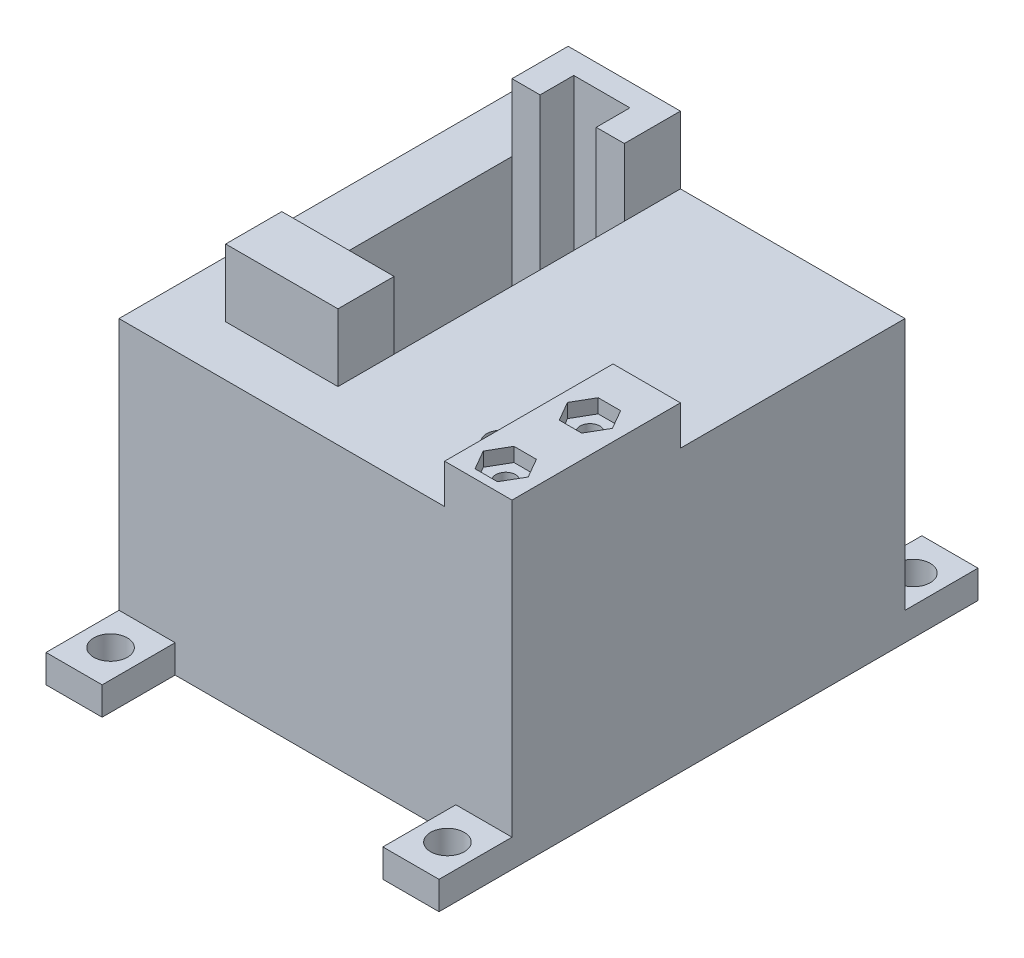
SolidWorks part; units mm, degrees
ref_plane "Front Plane" through (0, 0, 0) normal (0, 0, 1) x (1, 0, 0)
ref_plane "Top Plane" through (0, 0, 0) normal (0, 1, 0) x (1, 0, 0)
ref_plane "Right Plane" through (0, 0, 0) normal (1, 0, 0) x (0, 0, -1)
sketch "Sketch1" plane through (0, 0, 0) normal (0, 1, 0) x (1, 0, 0)
  line L1 (35, 35) -> (-35, 35)
  line L2 (35, 35) -> (35, -35)
  line L3 (35, -35) -> (-35, -35)
  line L4 (-35, 35) -> (-35, -35)
  line L5 (35, 35) -> (-35, -35) construction
  line L6 (35, -35) -> (-35, 35) construction
  point P0 (0, 0)
extrude "Boss-Extrude1" add sketch "Sketch1" along normal blind 50
sketch "Sketch2" plane through (0, 0, 0) normal (0, -1, 0) x (1, 0, 0)
  line L1 (0, 25) -> (-25, 25)
  line L2 (-25, 25) -> (-25, -25)
  line L3 (-25, -25) -> (25, -25)
  line L4 (0, 25) -> (25, 25)
  line L5 (25, 25) -> (25, -25)
extrude "Cut-Extrude1" cut sketch "Sketch2" against normal blind 40
sketch "Sketch3" plane through (0, 50, 0) normal (0, 1, 0) x (1, 0, 0)
  line L11 (-25, 25) -> (-5, 25)
  line L12 (-5, 25) -> (-5, -16)
  line L13 (-5, -16) -> (-25, -16)
  line L14 (-25, 25) -> (-25, -16)
extrude "Cut-Extrude2" cut sketch "Sketch3" against normal blind 40
sketch "Sketch4" plane through (0, 50, 0) normal (0, 1, 0) x (1, 0, 0)
  line L0 (-15, 25) -> (-15, 15)
  line L1 (-5, 25) -> (-25, 25) construction
  line L2 (-15, 15) -> (30, 15)
  line L4 (35, -35) -> (23, -35)
  line L6 (35, -35) -> (35, -5)
  line L8 (35, -5) -> (23, -5)
  line L9 (23, -35) -> (23, -5)
  line M24 (-35, -35) -> (35, -35)
  line M25 (35, -35) -> (35, 35)
extrude "Boss-Extrude2" add sketch "Sketch4" along normal blind 7 contours L9 L8 M24 M25
sketch "Sketch5" plane through (0, 57, 0) normal (0, 1, 0) x (1, 0, 0)
  line L3 (32.8817, -15) -> (30.8817, -18.4641)
  line L4 (30.8817, -18.4641) -> (26.8817, -18.4641)
  line L5 (26.8817, -18.4641) -> (24.8817, -15)
  line L6 (24.8817, -15) -> (26.8817, -11.5359)
  line L7 (26.8817, -11.5359) -> (30.8817, -11.5359)
  line L8 (30.8817, -11.5359) -> (32.8817, -15)
  line L9 (26.8817, -33.4641) -> (24.8817, -30)
  line L10 (24.8817, -30) -> (26.8817, -26.5359)
  line L11 (30.8817, -33.4641) -> (26.8817, -33.4641)
  line L12 (30.8817, -26.5359) -> (32.8817, -30)
  line L13 (32.8817, -30) -> (30.8817, -33.4641)
  line L14 (26.8817, -26.5359) -> (30.8817, -26.5359)
extrude "Cut-Extrude3" cut sketch "Sketch5" against normal blind 2.5
sketch "Sketch7" plane through (0, 50, 0) normal (0, 1, 0) x (1, 0, 0)
  line L0 (23, -35) -> (23, -20)
  line L1 (23, -35) -> (23, -5) construction
  circle A0 centre (18, -20) radius 2.5
extrude "Cut-Extrude4" cut sketch "Sketch7" against normal blind 52.5 contours A0
sketch "Sketch10" plane through (0, 0, 0) normal (0, -1, 0) x (1, 0, 0)
  line L1 (-25, -25) -> (25, -25) construction
  line L2 (-20, -25) -> (-20, -31)
  line L3 (-20, -31) -> (-10, -31)
  line L4 (-10, -31) -> (-10, -25)
  line L5 (-10, -25) -> (-20, -25)
extrude "Cut-Extrude6" cut sketch "Sketch10" against normal blind 55 contours L2 L3 L4 L5
sketch "Sketch11" plane through (0, 50, 0) normal (0, 1, 0) x (1, 0, 0)
  line L0 (-25, 25) -> (-25, 35)
  line L3 (-5, 25) -> (-5, 35)
  line L4 (-25, -16) -> (-25, -26)
  line L5 (-25, 35) -> (-5, 35)
  line L6 (-25, -26) -> (-5, -26)
  line L7 (-5, -26) -> (-5, -16)
  line L8 (-5, -16) -> (-25, -16)
  line M8 (-5, -16) -> (-25, -16)
  line M10 (-25, 25) -> (-20, 25)
  line M16 (35, 35) -> (-35, 35)
extrude "Boss-Extrude3" add sketch "Sketch11" along normal blind 12 contours L3 L0 M10 M16 | L6 L7 L4 M8
sketch "Sketch13" plane through (0, 0, 35) normal (0, 0, 1) x (1, 0, 0)
  line L0 (-35, 0) -> (-35, 5)
  line L1 (-35, 50) -> (-35, 0) construction
  line L2 (-35, 5) -> (-25, 5)
  line L3 (-25, 5) -> (-25, 0)
  line L4 (-35, 0) -> (35, 0) construction
  line L5 (35, 0) -> (35, 5)
  line L6 (35, 57) -> (35, 0) construction
  line L7 (35, 5) -> (25, 5)
  line L8 (-35, 0) -> (-25, 0)
  line L9 (35, 0) -> (25, 0)
  line L10 (25, 0) -> (25, 5)
extrude "Boss-Extrude4" add sketch "Sketch13" along normal blind 13
sketch "Sketch14" plane through (0, 0, -35) normal (0, 0, -1) x (-1, 0, 0)
  line L0 (-35, 0) -> (-35, 5)
  line L1 (-35, 0) -> (35, 0) construction
  line L2 (-35, 5) -> (-25, 5)
  line L3 (-25, 5) -> (-25, 0)
  line L4 (-25, 0) -> (-35, 0)
  line L5 (35, 0) -> (25, 0)
  line L6 (25, 0) -> (25, 5)
  line L7 (25, 5) -> (35, 5)
  line L8 (35, 50) -> (35, 0) construction
  line L9 (35, 5) -> (35, 0)
extrude "Boss-Extrude5" add sketch "Sketch14" along normal blind 13
sketch "Sketch15" plane through (0, 5, 0) normal (0, 1, 0) x (1, 0, 0)
  circle A0 centre (-29.8884, 41.355) radius 3
  circle A1 centre (-30, -41.5) radius 3
  circle A2 centre (30, -41.5) radius 3
  circle A3 centre (30, 41.5) radius 3
extrude "Cut-Extrude7" cut sketch "Sketch15" against normal blind 33
sketch "Sketch16" plane through (-35, 0, 0) normal (-1, 0, 0) x (0, 0, 1)
  line L0 (-10, 10) -> (-20, 10)
  line L4 (-48, 0) -> (48, 0) construction
  line L6 (-20, 0) -> (-20, 10)
  line L7 (-20, 10) -> (-15, 10)
  line L8 (-10, 0) -> (-10, 10)
  line L9 (-10, 0) -> (-20, 0)
  line M3 (-48, 0) -> (48, 0)
extrude "Cut-Extrude8" cut sketch "Sketch16" against normal blind 10 contours L8 L0 L6 M3
sketch "Sketch18" plane through (0, 54.5, 0) normal (0, 1, 0) x (1, 0, 0)
  circle A0 centre (28.8817, -15) radius 1.75
  circle A1 centre (28.8817, -30) radius 1.75
extrude "Cut-Extrude9" cut sketch "Sketch18" against normal blind 20
